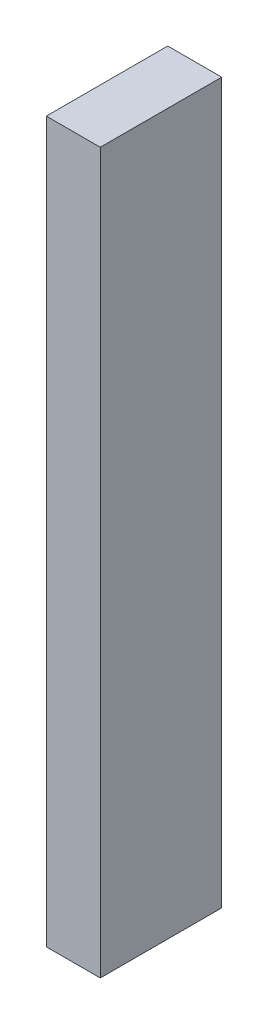
SolidWorks part; units mm, degrees
ref_plane "Top" through (0, 0, 0) normal (0, 0, 1) x (1, 0, 0)
ref_plane "Front" through (0, 0, 0) normal (0, 1, 0) x (1, 0, 0)
ref_plane "Right" through (0, 0, 0) normal (1, 0, 0) x (0, 0, -1)
sketch "Profile Sketch" plane through (-13.8341, 0, -105.7567) normal (0, 1, 0) x (-1, 0, 0)
  line L1 (-3, 0) -> (3, 0)
  line L2 (-3, 0) -> (-3, 13.5)
  line L3 (-3, 13.5) -> (3, 13.5)
  line L4 (3, 0) -> (3, 13.5)
  line L5 (0, 13.5) -> (0, 0) construction
  line L6 (-3, 6.75) -> (3, 6.75) construction
  point P128 (0, 6.75)
  dimension "Height" = 13.5
  dimension "Width" = 6
extrude "Profile Extrude" add sketch "Profile Sketch" along normal blind 80
